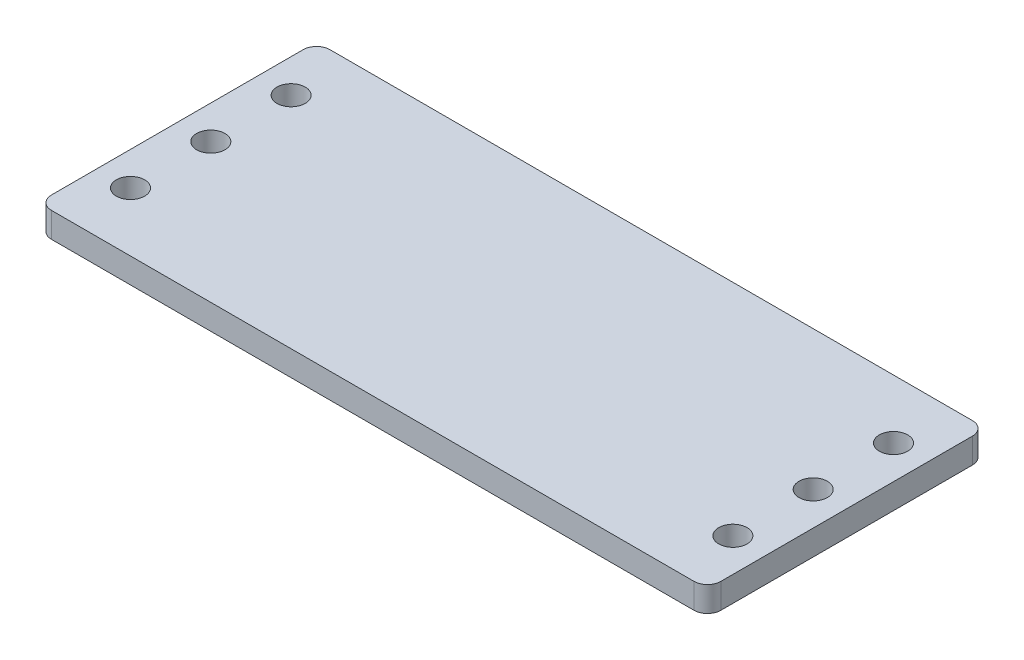
SolidWorks part; units mm, degrees
material "PE High Density Film"
ref_plane "Front Plane" through (0, 0, 0) normal (0, 0, 1) x (1, 0, 0)
ref_plane "Top Plane" through (0, 0, 0) normal (0, 1, 0) x (1, 0, 0)
ref_plane "Right Plane" through (0, 0, 0) normal (1, 0, 0) x (0, 0, -1)
sketch "Sketch1" plane through (0, 0, 0) normal (0, 1, 0) x (1, 0, 0)
  line L1 (-63.5, 26.416) -> (63.5, 26.416)
  line L2 (-63.5, 26.416) -> (-63.5, -26.416)
  line L3 (-63.5, -26.416) -> (63.5, -26.416)
  line L4 (63.5, 26.416) -> (63.5, -26.416)
  line L5 (-63.5, 26.416) -> (63.5, -26.416) construction
  line L6 (-63.5, -26.416) -> (63.5, 26.416) construction
  point P0 (0, 0)
  dimension "D1" = 127
  dimension "D2" = 52.832
extrude "Boss-Extrude1" add sketch "Sketch1" along normal blind 4.7625
fillet "Fillet1" radius 2.54 4 edges at (63.5, 2.3813, 26.416) (63.5, 2.3813, -26.416) (-63.5, 2.3813, -26.416) (-63.5, 2.3813, 26.416)
sketch "Sketch2" plane through (0, 0, 0) normal (0, -1, 0) x (1, 0, 0)
  line L0 (-60.96, 26.416) -> (60.96, 26.416) construction
  circle A0 centre (57.15, -15.24) radius 2.69
  circle A1 centre (57.15, 0) radius 2.69
  circle A2 centre (57.15, 15.24) radius 2.69
  dimension "D1" = 5.38
  dimension "D2" = 11.176
  dimension "D3" = 15.24
  dimension "D4" = 15.24
extrude "Cut-Extrude1" cut sketch "Sketch2" against normal through all
mirror "Mirror1" about plane through (0, 0, 0) normal (1, 0, 0) of "Cut-Extrude1"
